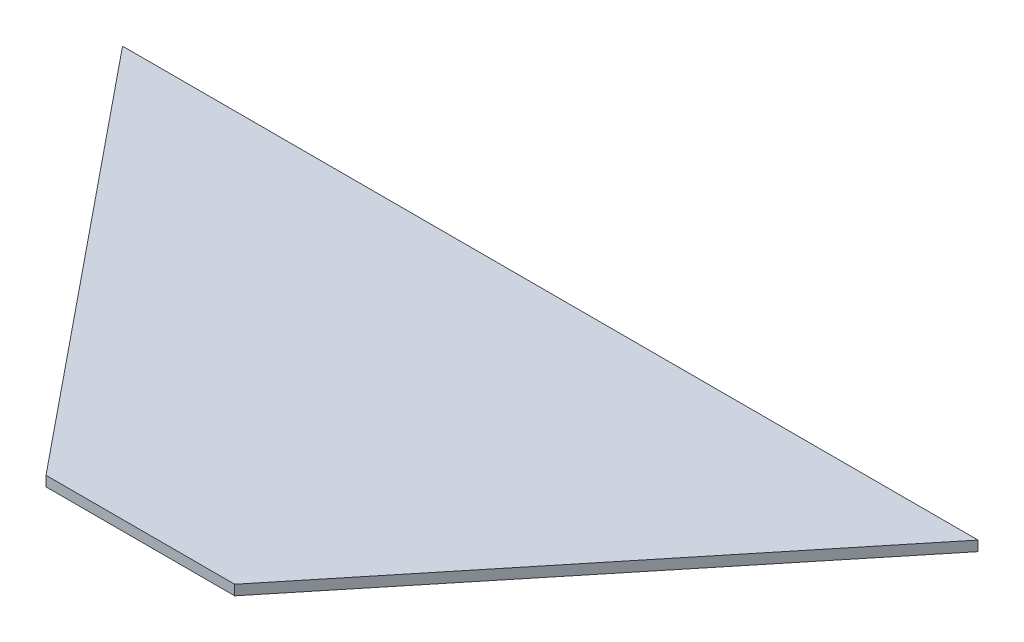
SolidWorks part; units mm, degrees
material "Сосна"
ref_plane "Спереди" through (0, 0, 0) normal (0, 0, 1) x (1, 0, 0)
ref_plane "Сверху" through (0, 0, 0) normal (0, 1, 0) x (1, 0, 0)
ref_plane "Справа" through (0, 0, 0) normal (1, 0, 0) x (0, 0, -1)
sketch3d "Трехмерный эскиз1"
  line L0 (-117.416, 10, 222.3293) -> (222.584, 10, 222.3293)
  line L5 (222.584, 10, 222.3293) -> (90.084, 10, 385.2519)
  line L6 (90.084, 10, 385.2519) -> (15.084, 10, 385.2519)
  line L7 (15.084, 10, 385.2519) -> (-117.416, 10, 222.3293)
  dimension "D1" = 10
  dimension "D4" = 75
  dimension "D5" = 340
  dimension "D6" = 210
  dimension "D7" = 210
extrude "Бобышка-Вытянуть1" add sketch "Трехмерный эскиз1" along direction (0, 1, 0) on the side against the normal blind 4
